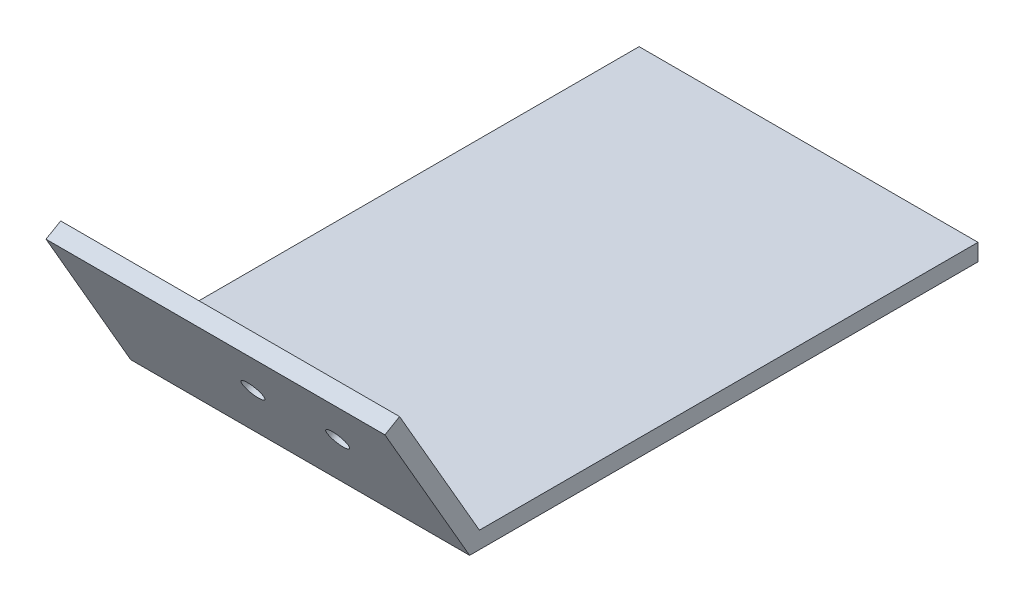
SolidWorks part; units mm, degrees
ref_plane "Front Plane" through (0, 0, 0) normal (0, 0, 1) x (1, 0, 0)
ref_plane "Top Plane" through (0, 0, 0) normal (0, 1, 0) x (1, 0, 0)
ref_plane "Right Plane" through (0, 0, 0) normal (1, 0, 0) x (0, 0, -1)
sketch "Sketch1" plane through (0, 0, 0) normal (1, 0, 0) x (0, 0, -1)
  line L0 (0, 0) -> (-25, 43.3013)
  line L1 (-25, 43.3013) -> (-20.6699, 45.8013)
  line L2 (-20.6699, 45.8013) -> (2.8868, 5)
  line L3 (2.8868, 5) -> (150, 5)
  line L4 (150, 5) -> (150, 0)
  line L5 (150, 0) -> (0, 0)
  dimension "D1" = 120
  dimension "D2" = 50
  dimension "D3" = 5
  dimension "D4" = 150
extrude "Boss-Extrude1" add sketch "Sketch1" along normal blind 100
sketch "Sketch2" plane through (0, 2.5, -4.3301) normal (0, 0.5, -0.866) x (-1, 0, 0)
  line L0 (-100, 2.8868) -> (0, 2.8868) construction
  line L1 (-100, 2.8868) -> (-100, 50) construction
  circle A0 centre (-75, 27.8868) radius 3.175
  circle A1 centre (-50, 27.8868) radius 3.175
  dimension "D3" = 6.35
  dimension "D1" = 25
  dimension "D2" = 25
  dimension "D4" = 25
extrude "Cut-Extrude1" cut sketch "Sketch2" against normal through all
